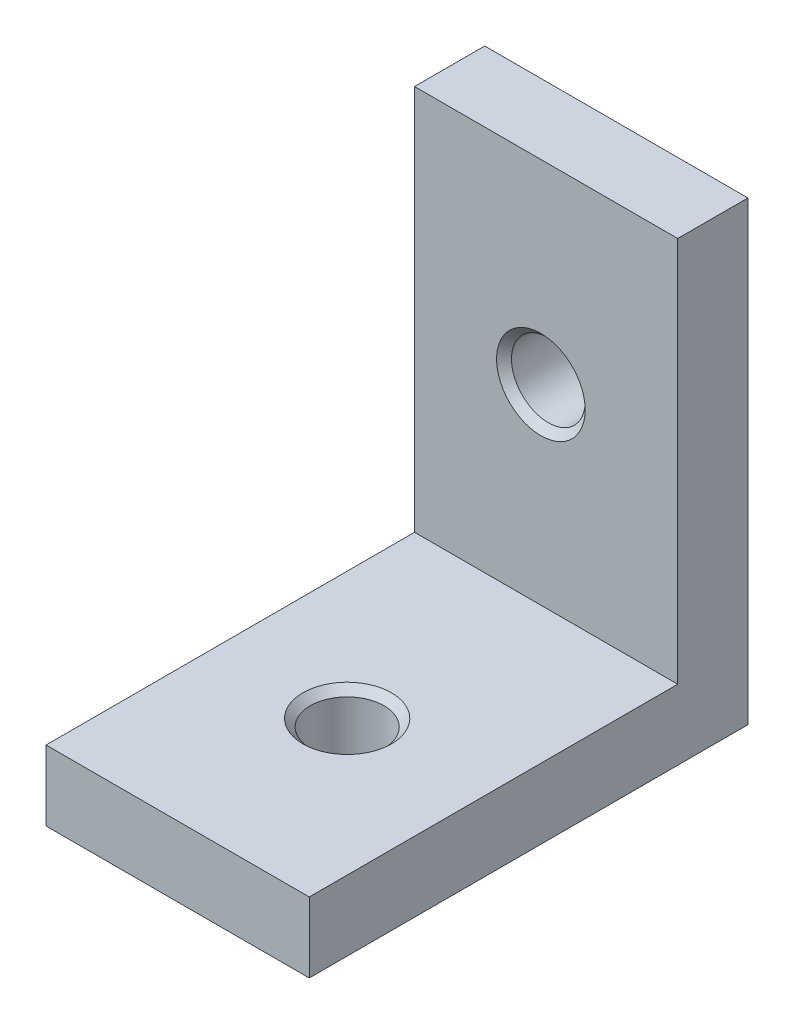
SolidWorks part; units mm, degrees
ref_plane "Front Plane" through (0, 0, 0) normal (0, 0, 1) x (1, 0, 0)
ref_plane "Top Plane" through (0, 0, 0) normal (0, 1, 0) x (1, 0, 0)
ref_plane "Right Plane" through (0, 0, 0) normal (1, 0, 0) x (0, 0, -1)
sketch "Sketch1" plane through (0, 0, 0) normal (0, 1, 0) x (1, 0, 0)
  line L1 (-29.9682, 12.6194) -> (-14.9682, 12.6194)
  line L2 (-29.9682, 12.6194) -> (-29.9682, -12.3806)
  line L3 (-29.9682, -12.3806) -> (-14.9682, -12.3806)
  line L4 (-14.9682, 12.6194) -> (-14.9682, -12.3806)
  line L5 (-29.9682, 12.6194) -> (-14.9682, -12.3806) construction
  line L6 (-29.9682, -12.3806) -> (-14.9682, 12.6194) construction
  line L11 (-21.9682, 14.2004) -> (-14.9682, 18.2004) construction
  line L12 (-21.9682, 18.2004) -> (-14.9682, 14.2004) construction
  point P4 (-22.4682, 0.1194)
  point P9 (-18.4682, 16.2004)
  dimension "D1" = 25
  dimension "D2" = 15
  dimension "D3" = 4
extrude "Boss-Extrude1" add sketch "Sketch1" along normal blind 4
sketch "Sketch2" plane through (0, 4, 0) normal (0, 1, 0) x (1, 0, 0)
  line L0 (-14.9682, -12.3806) -> (-14.9682, 12.6194) construction
  line L1 (-29.9682, 12.6194) -> (-14.9682, 12.6194)
  line L2 (-29.9682, 12.6194) -> (-29.9682, 8.6194)
  line L3 (-29.9682, 8.6194) -> (-14.9682, 8.6194)
  line L4 (-14.9682, 12.6194) -> (-14.9682, 8.6194)
  line L5 (-29.9682, 12.6194) -> (-14.9682, 8.6194) construction
  line L6 (-29.9682, 8.6194) -> (-14.9682, 12.6194) construction
  point P4 (-22.4682, 10.6194)
  dimension "D1" = 4
  dimension "D2" = 15
extrude "Boss-Extrude2" add sketch "Sketch2" along normal blind 22
hole_wizard "M5x0.8 Tapped Hole2" positions "3DSketch1" profile "Sketch3" tap size "M5x0.8" standard "ANSI Metric" end condition through all
sketch3d "3DSketch1"
  point P0 (-22.7034, 4, 2.4853)
  point P2 (-22.7683, 14.8924, -8.6194)
sketch "Sketch3" plane through (-22.7034, 4, 2.4853) normal (1, 0, 0) x (0, 0, 1)
  line L0 (0, 0) -> (0, 4)
  line L1 (0, 4) -> (2.1, 4)
  line L2 (2.1, 4) -> (2.1, 0.425)
  line L3 (2.1, 0.425) -> (2.525, 0)
  line L5 (2.525, 0) -> (0, 0)
  line L6 (-2.1, 0.425) -> (-2.525, 0) construction
  line L11 (0, -6.35) -> (0, 107.95) construction
  dimension "Thru Tap Drill Dia." = 4.2
  dimension "Thru Tap Drill Depth" = 4
  dimension "Near C'Sink Dia." = 5.05
  dimension "Near C'Sink Angle" = 90
cosmetic thread "Hole Thread1" parameters "D2"=5
cosmetic thread "Hole Thread2" parameters "D2"=5
